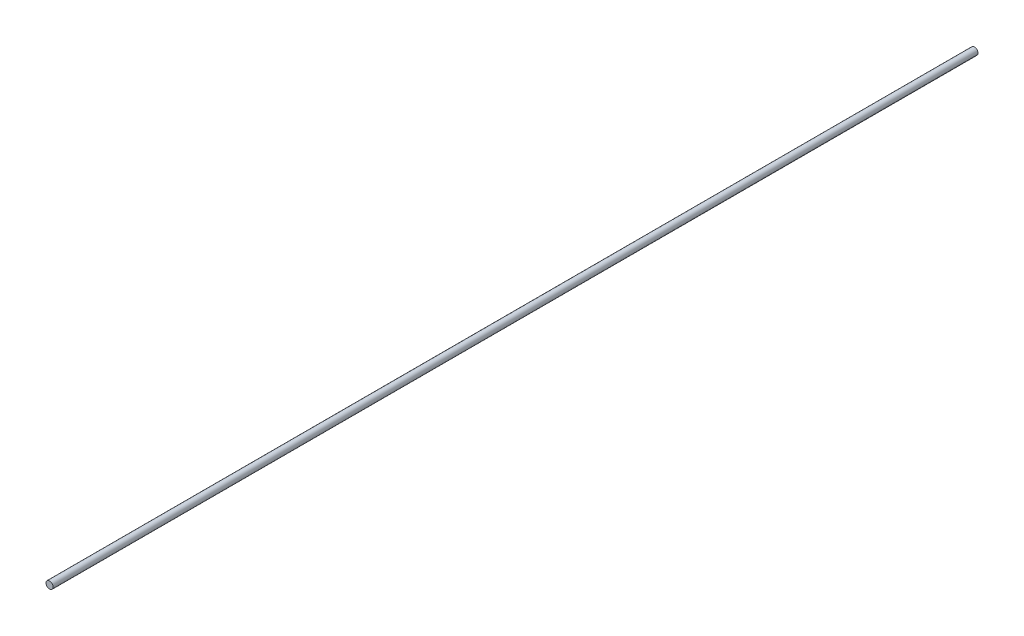
SolidWorks part; units mm, degrees
ref_plane "Front Plane" through (0, 0, 0) normal (0, 0, 1) x (1, 0, 0)
ref_plane "Top Plane" through (0, 0, 0) normal (0, 1, 0) x (1, 0, 0)
ref_plane "Right Plane" through (0, 0, 0) normal (1, 0, 0) x (0, 0, -1)
sketch "Sketch1" plane through (0, 0, 0) normal (0, 0, 1) x (1, 0, 0)
  circle A0 centre (0, 0) radius 2.5
extrude "Rod" add sketch "Sketch1" along normal blind 652
